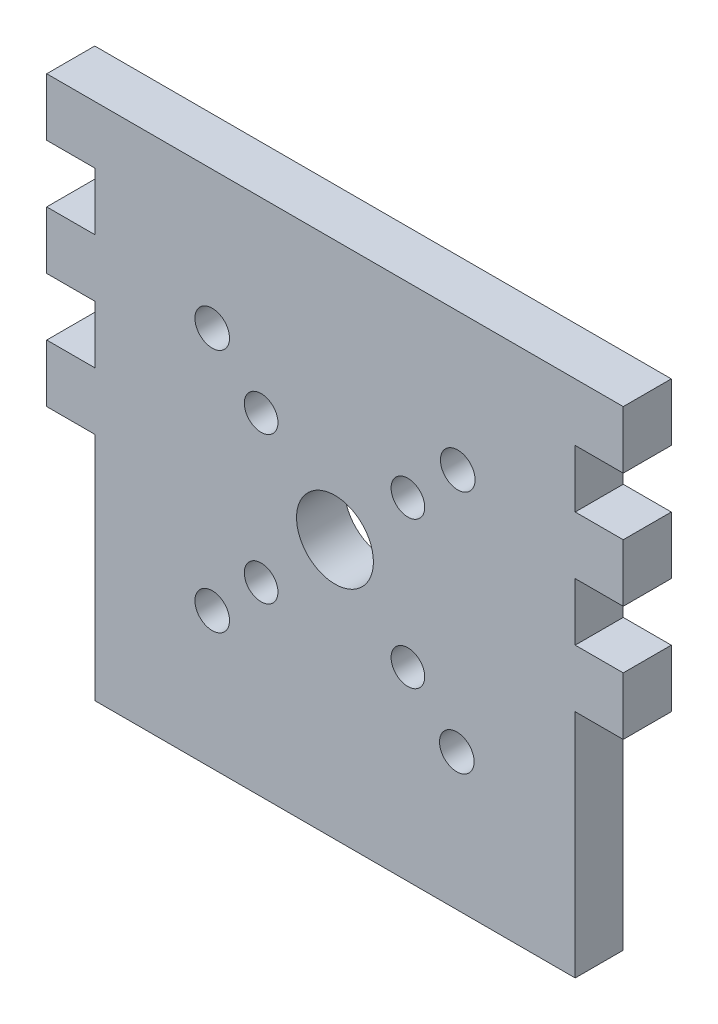
SolidWorks part; units mm, degrees
ref_plane "Front Plane" through (0, 0, 0) normal (0, 0, 1) x (1, 0, 0)
ref_plane "Top Plane" through (0, 0, 0) normal (0, 1, 0) x (1, 0, 0)
ref_plane "Right Plane" through (0, 0, 0) normal (1, 0, 0) x (0, 0, -1)
sketch "Sketch1" plane through (0, 0, 0) normal (0, 0, 1) x (1, 0, 0)
  line L1 (-37.8801, 17.0433) -> (38.3199, 17.0433)
  line L2 (-37.8801, 17.0433) -> (-37.8801, -59.1567)
  line L3 (-37.8801, -59.1567) -> (38.3199, -59.1567)
  line L4 (38.3199, 17.0433) -> (38.3199, -59.1567)
  dimension "D1" = 76.2
  dimension "D2" = 76.2
extrude "Boss-Extrude1" add sketch "Sketch1" along normal blind 6.35
sketch "Sketch2" plane through (0, 0, 6.35) normal (0, 0, 1) x (1, 0, 0)
  line L0 (-37.8801, 17.0433) -> (-31.5301, 17.0433)
  line L1 (38.3199, 17.0433) -> (-37.8801, 17.0433) construction
  line L2 (-31.5301, 17.0433) -> (-31.5301, 9.4233)
  line L3 (-31.5301, 9.4233) -> (-37.8801, 9.4233)
  line L4 (-37.8801, 17.0433) -> (-37.8801, -59.1567) construction
  line L5 (-37.8801, 9.4233) -> (-37.8801, 1.8033)
  line L6 (-37.8801, 1.8033) -> (-31.5301, 1.8033)
  line L7 (-31.5301, 1.8033) -> (-31.5301, -5.8167)
  line L8 (-31.5301, -5.8167) -> (-37.8801, -5.8167)
  line L9 (-37.8801, -5.8167) -> (-37.8801, -13.4367)
  line L10 (-37.8801, -13.4367) -> (-31.5301, -13.4367)
  line L11 (-31.5301, -13.4367) -> (-31.5301, -21.0567)
  line L12 (-31.5301, -21.0567) -> (-37.8801, -21.0567)
  line L13 (-37.8801, -21.0567) -> (-46.7258, -21.0567)
  line L14 (-37.8801, -21.0567) -> (-37.8801, -28.6767) [skipped]
  line L15 (-46.7258, -21.0567) -> (-46.7258, 17.0433)
  line L16 (-46.7258, 17.0433) -> (-37.8801, 17.0433)
  line L19 (47.1657, -21.0567) -> (47.1657, 17.0433)
  line L20 (38.3199, -21.0567) -> (47.1657, -21.0567)
  line L21 (31.9699, -21.0567) -> (38.3199, -21.0567)
  line L22 (31.9699, -13.4367) -> (31.9699, -21.0567)
  line L23 (38.3199, -13.4367) -> (31.9699, -13.4367)
  line L24 (38.3199, -5.8167) -> (38.3199, -13.4367)
  line L25 (31.9699, -5.8167) -> (38.3199, -5.8167)
  line L26 (31.9699, 1.8033) -> (31.9699, -5.8167)
  line L27 (38.3199, 1.8033) -> (31.9699, 1.8033)
  line L28 (38.3199, 9.4233) -> (38.3199, 1.8033)
  line L29 (31.9699, 9.4233) -> (38.3199, 9.4233)
  line L30 (31.9699, 17.0433) -> (31.9699, 9.4233)
  line L31 (38.3199, 17.0433) -> (31.9699, 17.0433)
  line L32 (47.1657, 17.0433) -> (38.3199, 17.0433)
  dimension "D1" = 7.62
  dimension "D2" = 7.62
  dimension "D3" = 6.35
  dimension "D4" = 6.35
  dimension "D6" = 38.1
  dimension "D5" = 3
extrude "Cut-Extrude1" cut sketch "Sketch2" against normal blind 6.35
sketch "Sketch3" plane through (0, 0, 6.35) normal (0, 0, 1) x (1, 0, 0)
  line L1 (-31.5301, -21.0567) -> (-37.8801, -21.0567)
  line L2 (-31.5301, -21.0567) -> (-31.5301, -59.1567)
  line L3 (-31.5301, -59.1567) -> (-37.8801, -59.1567)
  line L4 (-37.8801, -21.0567) -> (-37.8801, -59.1567)
  line L5 (31.9699, -21.0567) -> (38.3199, -21.0567)
  line L6 (31.9699, -21.0567) -> (31.9699, -59.1567)
  line L7 (31.9699, -59.1567) -> (38.3199, -59.1567)
  line L8 (38.3199, -21.0567) -> (38.3199, -59.1567)
extrude "Cut-Extrude2" cut sketch "Sketch3" against normal blind 6.35
sketch "Sketch4" plane through (0, 0, 6.35) normal (0, 0, 1) x (1, 0, 0)
  line L0 (-31.5301, -13.4367) -> (-31.5301, -21.0567)
  line L1 (-31.5301, -59.1567) -> (-31.5301, -13.4367) construction
  line L2 (-31.5301, -21.0567) -> (-37.8801, -21.0567)
  line L3 (-37.8801, -21.0567) -> (-37.8801, -28.6767)
  line L4 (-37.8801, -28.6767) -> (-31.5301, -28.6767)
  line L5 (-31.5301, -21.0567) -> (-31.5301, -28.6767)
  line L6 (0.2199, 17.0433) -> (0.2199, -59.1567)
  line L7 (31.9699, 17.0433) -> (-31.5301, 17.0433) construction
  line L8 (-31.5301, -59.1567) -> (31.9699, -59.1567) construction
  line L9 (31.9699, -21.0567) -> (38.3199, -21.0567)
  line L10 (38.3199, -21.0567) -> (38.3199, -28.6767)
  line L11 (38.3199, -28.6767) -> (31.9699, -28.6767)
  line L12 (31.9699, -21.0567) -> (31.9699, -28.6767)
  line M6 (-31.5301, -13.4367) -> (-31.5301, -59.1567)
  line M8 (31.9699, -59.1567) -> (31.9699, -13.4367)
  dimension "D1" = 7.62
  dimension "D2" = 7.62
  dimension "D3" = 6.35
  dimension "D4" = 6.35
extrude "Boss-Extrude3" add sketch "Sketch4" against normal blind 6.35 contours L3 L4 L2 M6 | L11 L10 L9 M8
sketch "Sketch5" plane through (0, 17.0433, 0) normal (0, 1, 0) x (1, 0, 0)
  line L1 (-31.5301, 0) -> (31.9699, 0)
  line L2 (-31.5301, 0) -> (-31.5301, -6.35)
  line L3 (-31.5301, -6.35) -> (31.9699, -6.35)
  line L4 (31.9699, 0) -> (31.9699, -6.35)
extrude "Cut-Extrude3" cut sketch "Sketch5" against normal blind 7.62
sketch "Sketch6" plane through (0, 0, 6.35) normal (0, 0, 1) x (1, 0, 0)
  line L0 (-31.5301, -59.1567) -> (31.9699, -59.1567) construction
  circle A0 centre (0.2199, -24.8667) radius 5.08
  circle A1 centre (-9.5416, -34.6282) radius 2.2225
  circle A5 centre (-16.0057, -8.7638) radius 2.286
  circle A10 centre (-9.5414, -15.2311) radius 2.2225
  circle A11 centre (9.8557, -15.2313) radius 2.2225
  circle A12 centre (9.8555, -34.6285) radius 2.2225
  circle A13 centre (16.4455, -8.7638) radius 2.286
  circle A15 centre (16.3232, -41.0928) radius 2.286
  circle A16 centre (-16.0057, -41.0928) radius 2.286
  circle A17 centre (16.3232, -8.7638) radius 2.286 [skipped]
  point P16 (0.6912, -25.9139)
  point P26 (-0.068, -25.1546)
  point P28 (0.1571, -24.9298)
  point P29 (0.1587, -24.9283)
  dimension "D3" = 10.16
  dimension "D6" = 4.445
  dimension "D8" = 4.572
  dimension "D1" = 34.29
  dimension "D2" = 31.75
  dimension "D4" = 13.8049
  dimension "D5" = 4
  dimension "D7" = 13.716
  dimension "D9" = 13.6268
  dimension "D10" = 13.7163
  dimension "D11" = 9.144
  dimension "D12" = 6.4643
  dimension "D13" = 6.4673
  dimension "D14" = 4
extrude "Cut-Extrude4" cut sketch "Sketch6" against normal through all
